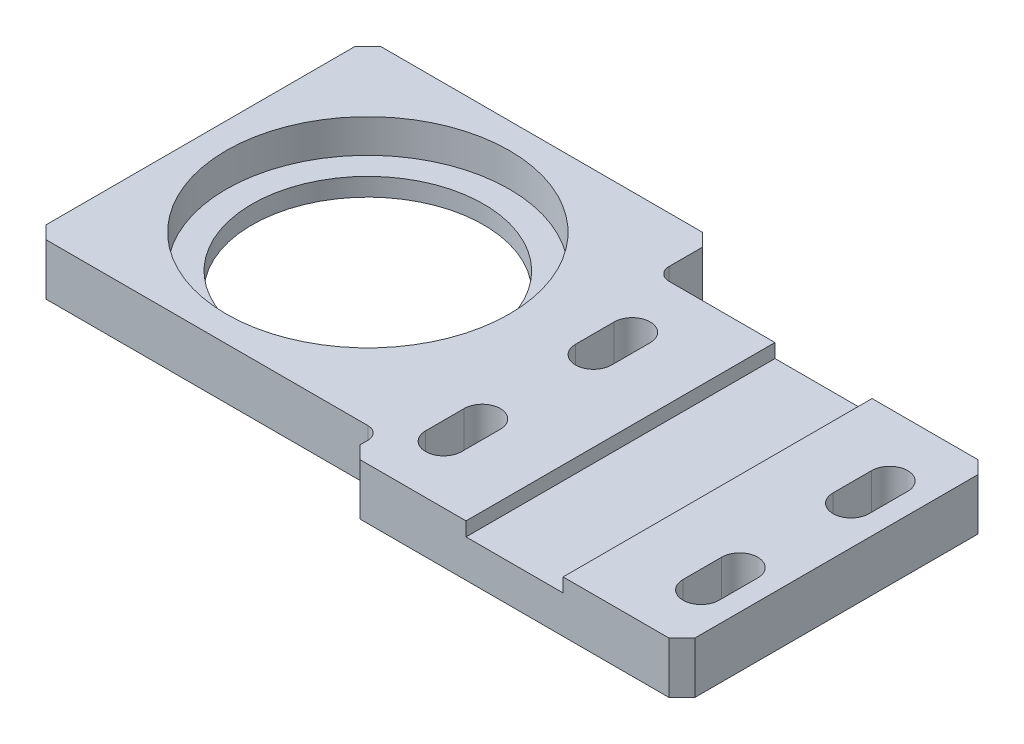
SolidWorks part; units mm, degrees
ref_plane "前视基准面" through (0, 0, 0) normal (0, 0, 1) x (1, 0, 0)
ref_plane "上视基准面" through (0, 0, 0) normal (0, 1, 0) x (1, 0, 0)
ref_plane "右视基准面" through (0, 0, 0) normal (1, 0, 0) x (0, 0, -1)
sketch "草图2" plane through (0, 0, 0) normal (0, 1, 0) x (1, 0, 0)
  line L0 (0, 0) -> (135, 0)
  line L1 (135, 0) -> (135, -23)
  line L2 (135, -23) -> (265, -23)
  line L3 (265, -23) -> (265, -143)
  line L4 (265, -143) -> (135, -143)
  line L5 (135, -143) -> (135, -130)
  line L6 (135, -130) -> (0, -130)
  line L7 (0, -130) -> (0, 0)
  point P9 (200, -143)
  dimension "D1" = 130
  dimension "D2" = 120
  dimension "D3" = 143
  dimension "D4" = 135
  dimension "D5" = 130
extrude "凸台-拉伸1" add sketch "草图2" along normal blind 20
sketch "草图3" plane through (0, 20, 0) normal (0, 1, 0) x (1, 0, 0)
  line L0 (0, 0) -> (0, -130) construction
  circle A0 centre (65, -65) radius 45
  point P4 (0, 0)
  point P5 (0, -65)
  dimension "D1" = 90
  dimension "D2" = 65
extrude "切除-拉伸1" cut sketch "草图3" against normal through all
sketch "草图4" plane through (0, 20, 0) normal (0, 1, 0) x (1, 0, 0)
  circle A0 centre (65, -65) radius 55
  dimension "D1" = 110
extrude "切除-拉伸2" cut sketch "草图4" against normal blind 13
sketch "草图5" plane through (0, 20, 0) normal (0, 1, 0) x (1, 0, 0)
  line L0 (181.1483, -23) -> (181.1483, -143)
  line L1 (265, -23) -> (135, -23) construction
  line L2 (135, -143) -> (265, -143) construction
  line L3 (218.8517, -23) -> (218.8517, -143)
  line L4 (200, -23) -> (200, -143) construction
  line L5 (265, -143) -> (265, -23) construction
  line L6 (181.1483, -23) -> (218.8517, -23)
  line L7 (218.8517, -143) -> (181.1483, -143)
  dimension "D1" = 65
extrude "切除-拉伸3" cut sketch "草图5" against normal blind 5.4
sketch "草图6" plane through (0, 20, 0) normal (0, 1, 0) x (1, 0, 0)
  line L0 (265, -83) -> (145.3453, -83) construction
  line L1 (265, -143) -> (265, -23) construction
  line L2 (200, -23) -> (200, -143) construction
  line L3 (218.8517, -23) -> (181.1483, -23) construction
  line L4 (181.1483, -143) -> (218.8517, -143) construction
  line L5 (150, -47.3125) -> (150, -62.3125) construction
  line L6 (157, -47.3125) -> (157, -62.3125)
  line L7 (143, -47.3125) -> (143, -62.3125)
  line L8 (150, -105.5582) -> (150, -120.5582) construction
  line L9 (157, -105.5582) -> (157, -120.5582)
  line L10 (143, -105.5582) -> (143, -120.5582)
  line L11 (250, -47.3125) -> (250, -62.3125) construction
  line L12 (257, -47.3125) -> (257, -62.3125)
  line L13 (243, -47.3125) -> (243, -62.3125)
  line L14 (250, -105.5582) -> (250, -120.5582) construction
  line L15 (257, -105.5582) -> (257, -120.5582)
  line L16 (243, -105.5582) -> (243, -120.5582)
  arc A0 (157, -47.3125) -> (143, -47.3125) centre (150, -47.3125) ccw
  arc A1 (143, -62.3125) -> (157, -62.3125) centre (150, -62.3125) ccw
  arc A2 (157, -105.5582) -> (143, -105.5582) centre (150, -105.5582) ccw
  arc A3 (143, -120.5582) -> (157, -120.5582) centre (150, -120.5582) ccw
  arc A4 (257, -47.3125) -> (243, -47.3125) centre (250, -47.3125) ccw
  arc A5 (243, -62.3125) -> (257, -62.3125) centre (250, -62.3125) ccw
  arc A6 (257, -105.5582) -> (243, -105.5582) centre (250, -105.5582) ccw
  arc A7 (243, -120.5582) -> (257, -120.5582) centre (250, -120.5582) ccw
  point P12 (150, -54.8125)
  point P17 (150, -113.0582)
  point P24 (250, -54.8125)
  point P31 (250, -113.0582)
  point P38 (0, 0)
  point P39 (0, 0)
  point P40 (0, 0)
  point P41 (0, 0)
  point P42 (0, 0)
  dimension "D2" = 29
  dimension "D1" = 14
  dimension "D3" = 100
extrude "切除-拉伸4" cut sketch "草图6" against normal through all
fillet "圆角1" radius 5 2 edges at (135, 10, 23) (135, 10, 130)
chamfer "倒角1" distance 5 6 edges at (265, 10, 23) (265, 10, 143) (135, 10, 143) (135, 10, 0) (0, 10, 130) (0, 10, 0)
